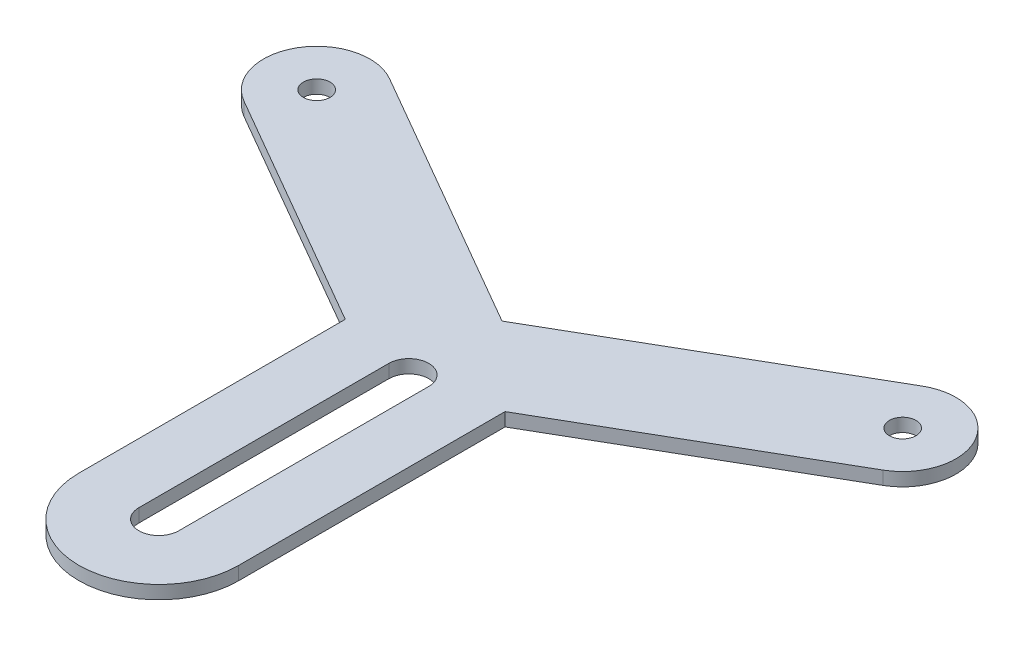
SolidWorks part; units mm, degrees
ref_plane "Front" through (0, 0, 0) normal (0, 0, 1) x (1, 0, 0)
ref_plane "Top" through (0, 0, 0) normal (0, 1, 0) x (1, 0, 0)
ref_plane "Right" through (0, 0, 0) normal (1, 0, 0) x (0, 0, -1)
sketch "Sketch1" plane through (0, 0, 0) normal (0, 1, 0) x (1, 0, 0)
  line L0 (-139.7, 0) -> (0, 0) construction
  line L1 (0, 0) -> (139.7, 0) construction
  line L2 (-127, 21.997) -> (0, -51.3264)
  line L3 (-152.4, -21.997) -> (-38.1, -87.9882)
  line L4 (0, 0) -> (0, -190.9123) construction
  line L5 (-38.1, -87.9882) -> (-38.1, -214.9882)
  line L6 (127, 21.997) -> (0, -51.3264)
  line L7 (38.1, -87.9882) -> (38.1, -214.9882)
  line L8 (152.4, -21.997) -> (38.1, -87.9882)
  line L9 (0, -214.9882) -> (0, -95.7764) construction
  line L10 (-9.525, -214.9882) -> (-9.525, -95.7764)
  line L11 (9.525, -214.9882) -> (9.525, -95.7764)
  circle A0 centre (-139.7, 0) radius 6.35
  circle A1 centre (139.7, 0) radius 6.35
  arc A2 (-127, 21.997) -> (-152.4, -21.997) centre (-139.7, 0) ccw
  arc A3 (127, 21.997) -> (152.4, -21.997) centre (139.7, 0) cw
  arc A4 (-38.1, -214.9882) -> (38.1, -214.9882) centre (0, -214.9882) ccw
  arc A5 (-9.525, -214.9882) -> (9.525, -214.9882) centre (0, -214.9882) ccw
  arc A6 (9.525, -95.7764) -> (-9.525, -95.7764) centre (0, -95.7764) ccw
  point P17 (0, -155.3823)
  point P23 (0, -253.0882)
  dimension "D2" = 12.7
  dimension "D1" = 279.4
  dimension "D3" = 30
  dimension "D4" = 50.8
  dimension "D5" = 38.1
  dimension "D6" = 44.45
  dimension "D7" = 38.1
  dimension "D8" = 127
  dimension "D9" = 19.05
extrude "Boss-Extrude1" add sketch "Sketch1" along normal blind 6.35
